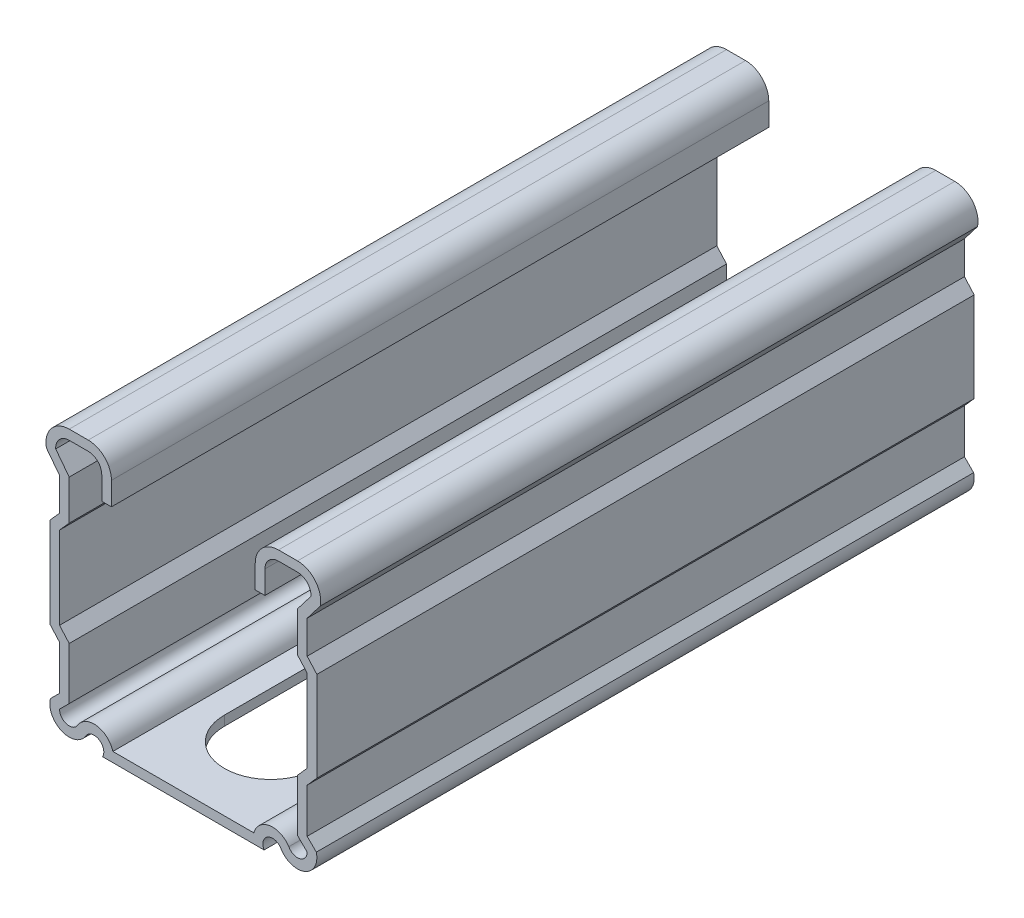
SolidWorks part; units mm, degrees
ref_plane "Plane1" through (0, 0, 0) normal (0, 0, 1) x (1, 0, 0)
ref_plane "Plane2" through (0, 0, 0) normal (0, 1, 0) x (1, 0, 0)
ref_plane "Plane3" through (0, 0, 0) normal (1, 0, 0) x (0, 0, -1)
sketch "Sketch1" plane through (0, 0, 0) normal (0, 0, 1) x (1, 0, 0)
  line L0 (17.6403, 16.3393) -> (19.7299, 19.0635)
  line L1 (17.6403, -13.9795) -> (19.1389, -15.4781)
  line L2 (-17.6403, -13.9795) -> (-19.1389, -15.4781)
  line L4 (-17.6403, -13.9795) -> (-17.6403, -5.9368)
  line L5 (17.6403, 21.2598) -> (14.7033, 21.2598)
  line L6 (12.6111, 19.1676) -> (12.6111, 15.6147)
  line L7 (-17.6403, -5.9368) -> (-19.1389, -4.2539)
  line L8 (-12.6111, 19.1676) -> (-12.6111, 15.6147)
  line L9 (0, 10.16) -> (0, -7.62) construction
  line L10 (-19.1389, -4.2539) -> (-19.1389, 8.4957)
  line L11 (-17.6403, 10.1786) -> (-19.1389, 8.4957)
  line L12 (-17.6403, 10.1786) -> (-17.6403, 16.3393)
  line L13 (-17.6403, 16.3393) -> (-19.7299, 19.0635)
  line L14 (-17.6403, 21.2598) -> (-14.7033, 21.2598)
  line L16 (17.6403, -13.9795) -> (17.6403, -5.9368)
  line L17 (17.6403, 10.1786) -> (17.6403, 16.3393)
  line L18 (-11.1125, 19.1676) -> (-11.1125, 15.6147)
  line L19 (-17.6403, 22.7584) -> (-14.7033, 22.7584)
  line L20 (-19.1389, 15.8307) -> (-21.1624, 18.4689)
  line L21 (-19.1389, 10.7491) -> (-19.1389, 15.8307)
  line L22 (-19.1389, 10.7491) -> (-20.6375, 9.0662)
  line L23 (-20.6375, -4.8244) -> (-20.6375, 9.0662)
  line L24 (-19.1389, -6.5073) -> (-20.6375, -4.8244)
  line L25 (19.1389, -4.2539) -> (19.1389, 8.4957)
  line L26 (-19.1389, -13.3588) -> (-19.1389, -6.5073)
  line L27 (-19.1389, -13.3588) -> (-20.5535, -14.7733)
  line L28 (11.1125, 19.1676) -> (11.1125, 15.6147)
  line L29 (17.6403, 22.7584) -> (14.7033, 22.7584)
  line L30 (19.1389, 15.8307) -> (21.1624, 18.4689)
  line L31 (19.1389, 10.7491) -> (19.1389, 15.8307)
  line L32 (19.1389, 10.7491) -> (20.6375, 9.0662)
  line L33 (20.6375, -4.8244) -> (20.6375, 9.0662)
  line L34 (19.1389, -6.5073) -> (20.6375, -4.8244)
  line L35 (19.1389, -13.3588) -> (19.1389, -6.5073)
  line L36 (19.1389, -13.3588) -> (20.5535, -14.7733)
  line L37 (17.6403, -5.9368) -> (19.1389, -4.2539)
  line L38 (-12.4806, -18.5166) -> (12.4806, -18.5166)
  line L39 (17.6403, 10.1786) -> (19.1389, 8.4957)
  line L41 (-10.899, -17.018) -> (10.899, -17.018)
  line L42 (-12.6111, 15.6147) -> (-11.1125, 15.6147)
  line L43 (11.1125, 15.6147) -> (12.6111, 15.6147)
  arc A0 (19.1389, -15.4781) -> (16.3052, -16.1588) centre (17.6403, -15.4781) cw
  arc A1 (16.3052, -16.1588) -> (10.899, -17.018) centre (13.7938, -17.7947) ccw
  arc A2 (-16.4143, -16.3399) -> (-10.899, -17.018) centre (-13.7938, -17.7947) cw
  arc A3 (-19.1389, -15.4781) -> (-16.4143, -16.3399) centre (-17.6403, -15.4781) ccw
  arc A4 (-17.6403, 21.2598) -> (-19.7299, 19.0635) centre (-17.6403, 19.1676) ccw
  arc A5 (-12.6111, 19.1676) -> (-14.7033, 21.2598) centre (-14.7033, 19.1676) ccw
  arc A6 (17.6403, 21.2598) -> (19.7299, 19.0635) centre (17.6403, 19.1676) cw
  arc A7 (12.6111, 19.1676) -> (14.7033, 21.2598) centre (14.7033, 19.1676) cw
  arc A8 (-11.1125, 19.1676) -> (-14.7033, 22.7584) centre (-14.7033, 19.1676) ccw
  arc A9 (-17.6403, 22.7584) -> (-21.1624, 18.4689) centre (-17.6403, 19.1676) ccw
  arc A10 (-20.5535, -14.7733) -> (-15.0198, -16.9329) centre (-17.6403, -15.4781) ccw
  arc A11 (11.1125, 19.1676) -> (14.7033, 22.7584) centre (14.7033, 19.1676) cw
  arc A12 (17.6403, 22.7584) -> (21.1624, 18.4689) centre (17.6403, 19.1676) cw
  arc A13 (20.5535, -14.7733) -> (15.0198, -16.9329) centre (17.6403, -15.4781) cw
  arc A14 (15.0198, -16.9329) -> (12.4806, -18.5166) centre (13.7938, -17.7947) ccw
  arc A15 (-15.0198, -16.9329) -> (-12.4806, -18.5166) centre (-13.7938, -17.7947) cw
  dimension "D9" = 7.1437
  dimension "base" = 18.5166
  dimension "D5" = 9.525
  dimension "ToeHt" = 22.7584
  dimension "D6" = 22.225
  dimension "D8" = 15.4781
  dimension "D12" = 41.275
  dimension "D14" = 13.6922
  dimension "D15" = 13.8906
extrude "Base-Extrude" add sketch "Sketch1" along normal blind 101.6
extrude "Slot" cut sketch "Sketch2" against normal through all
sketch "Sketch2" plane through (-0.0935, -18.5166, -16.4661) normal (0, -1, 0) x (1, 0, 0)
  line L0 (7.2372, 53.7723) -> (7.2372, 39.4848)
  line L1 (-7.0503, 39.4848) -> (-7.0503, 53.7723)
  arc A0 (-7.0503, 39.4848) -> (7.2372, 39.4848) centre (0.0935, 39.4848) ccw
  arc A1 (7.2372, 53.7723) -> (-7.0503, 53.7723) centre (0.0935, 53.7723) ccw
  dimension "D3" = 14.2875
  dimension "D1" = 23.0188
  dimension "D2" = 14.2875
pattern_linear "LPattern1" count 2 spacing 50.8 along (0, 0, 1) of "Slot"
equation "\"D1@LPattern1\" = \"D1@Base-Extrude\" / \"D3@LPattern1\""
